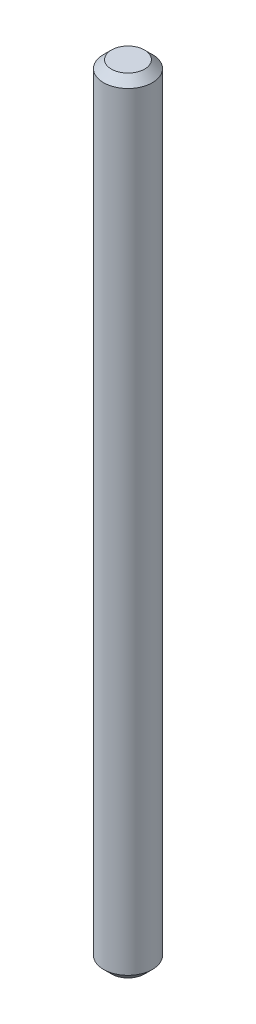
SolidWorks part; units mm, degrees
ref_plane "Front Plane" through (0, 0, 0) normal (0, 0, 1) x (1, 0, 0)
ref_plane "Top Plane" through (0, 0, 0) normal (0, 1, 0) x (1, 0, 0)
ref_plane "Right Plane" through (0, 0, 0) normal (1, 0, 0) x (0, 0, -1)
ref_plane "Plane1" through (0, 0, 0) normal (0, 0, -1) x (-1, 0, 0)
sketch "Sketch1" plane through (0, 0, 0) normal (0, 0, -1) x (-1, 0, 0)
  line L0 (-1.0757, 0) -> (0, 0)
  line L1 (0, 0) -> (0, 50.8)
  line L2 (0, 50.8) -> (-1.0757, 50.8)
  line L3 (-1.0757, 50.8) -> (-1.5837, 50.292)
  line L4 (-1.5837, 50.292) -> (-1.5837, 0.508)
  line L5 (-1.5837, 0.508) -> (-1.0757, 0)
  line L6 (0, 0) -> (0, 50.8) construction
revolve "Revolve1" add sketch "Sketch1" angle 360 about L6
